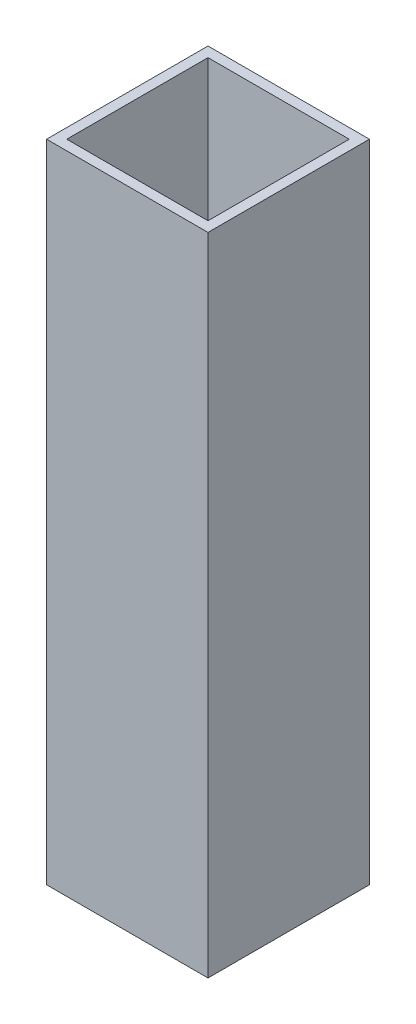
SolidWorks part; units mm, degrees
ref_plane "Front Plane" through (0, 0, 0) normal (0, 0, 1) x (1, 0, 0)
ref_plane "Top Plane" through (0, 0, 0) normal (0, 1, 0) x (1, 0, 0)
ref_plane "Right Plane" through (0, 0, 0) normal (1, 0, 0) x (0, 0, -1)
sketch "Sketch1" plane through (0, 0, 0) normal (0, 1, 0) x (1, 0, 0)
  line L1 (-12.7, -12.7) -> (12.7, -12.7)
  line L2 (-12.7, -12.7) -> (-12.7, 12.7)
  line L3 (-12.7, 12.7) -> (12.7, 12.7)
  line L4 (12.7, -12.7) -> (12.7, 12.7)
  line L5 (-12.7, -12.7) -> (12.7, 12.7) construction
  line L6 (-12.7, 12.7) -> (12.7, -12.7) construction
  line L7 (-11.1125, -11.1125) -> (11.1125, -11.1125)
  line L8 (-11.1125, -11.1125) -> (-11.1125, 11.1125)
  line L9 (-11.1125, 11.1125) -> (11.1125, 11.1125)
  line L10 (11.1125, -11.1125) -> (11.1125, 11.1125)
  line L11 (-11.1125, -11.1125) -> (11.1125, 11.1125) construction
  line L12 (-11.1125, 11.1125) -> (11.1125, -11.1125) construction
  point P0 (0, 0)
  point P6 (0, 0)
  dimension "D1" = 25.4
  dimension "D2" = 1.5875
extrude "Boss-Extrude1" add sketch "Sketch1" along normal blind 101.6
